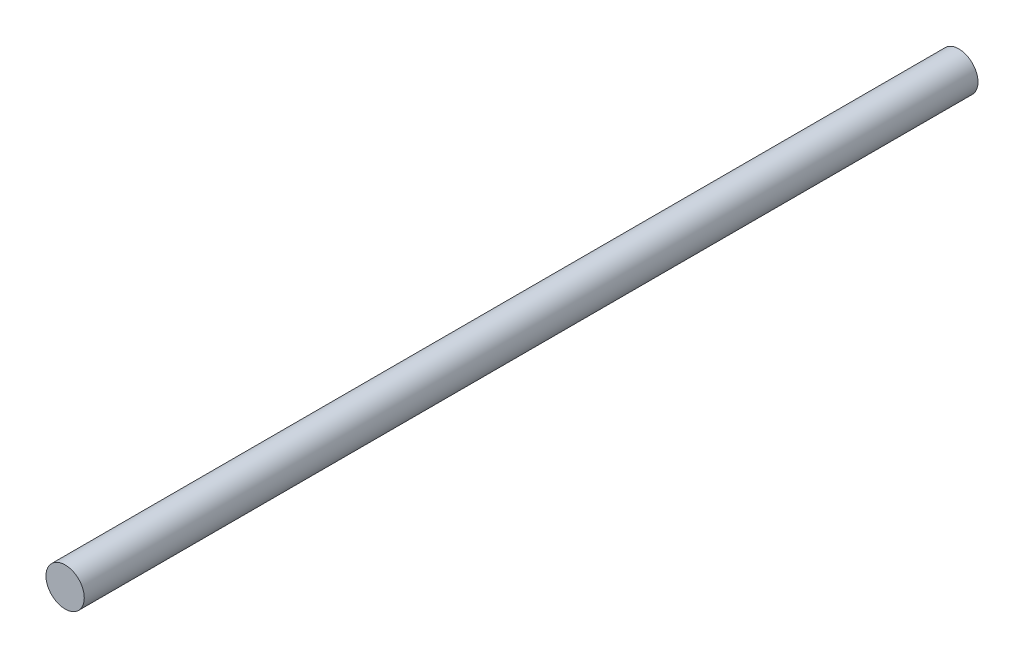
SolidWorks part; units mm, degrees
ref_plane "Front Plane" through (0, 0, 0) normal (0, 0, 1) x (1, 0, 0)
ref_plane "Top Plane" through (0, 0, 0) normal (0, 1, 0) x (1, 0, 0)
ref_plane "Right Plane" through (0, 0, 0) normal (1, 0, 0) x (0, 0, -1)
sketch "Sketch1" plane through (0, 0, 0) normal (0, 0, 1) x (1, 0, 0)
  circle A0 centre (0, 0) radius 7.5
  dimension "D1" = 15
extrude "Boss-Extrude2" add sketch "Sketch1" against normal blind 350 contours A0
